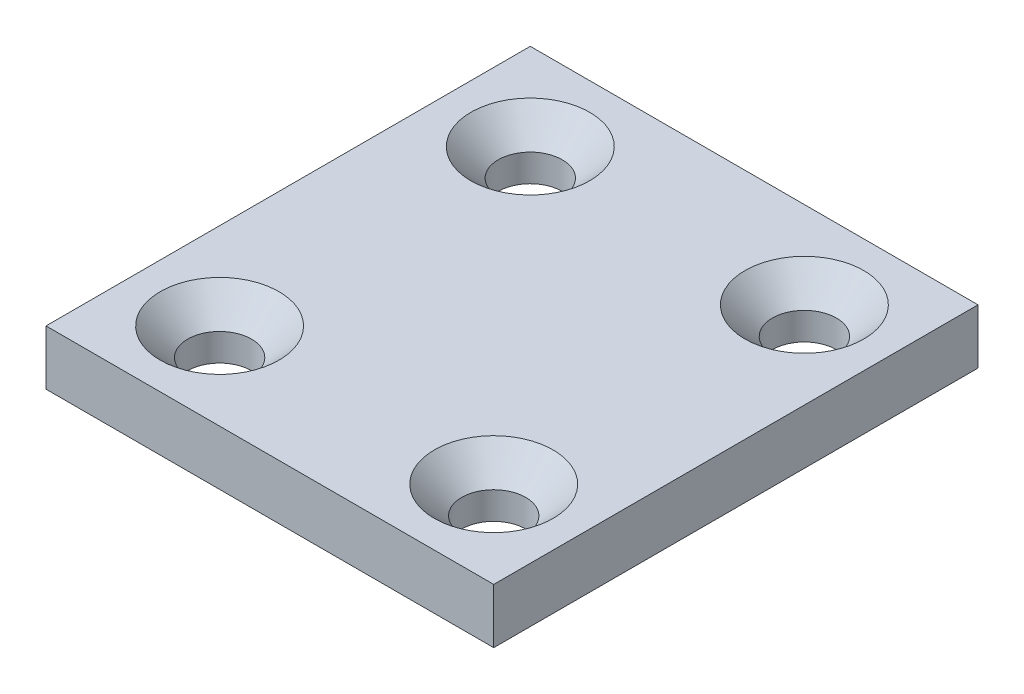
SolidWorks part; units mm, degrees
ref_plane "前视基准面" through (0, 0, 0) normal (0, 0, 1) x (1, 0, 0)
ref_plane "上视基准面" through (0, 0, 0) normal (0, 1, 0) x (1, 0, 0)
ref_plane "右视基准面" through (0, 0, 0) normal (1, 0, 0) x (0, 0, -1)
sketch "草图1" plane through (0, 0, 0) normal (0, 1, 0) x (1, 0, 0)
  line L1 (-4.75, -4.75) -> (19.75, -4.75)
  line L2 (-4.75, -4.75) -> (-4.75, 21.75)
  line L3 (-4.75, 21.75) -> (19.75, 21.75)
  line L4 (19.75, -4.75) -> (19.75, 21.75)
  circle A0 centre (0, 0) radius 1.75
  circle A1 centre (15, 0) radius 1.75
  circle A2 centre (0, 17) radius 1.75
  circle A3 centre (15, 17) radius 1.75
  dimension "D2" = 3.5
  dimension "D3" = 3.5
  dimension "D5" = 3.5
  dimension "D6" = 3.5
  dimension "D10" = 4.75
  dimension "D1" = 15
  dimension "D4" = 15
  dimension "D7" = 17
  dimension "D8" = 24.5
  dimension "D9" = 26.5
  dimension "D11" = 4.75
extrude "凸台-拉伸1" add sketch "草图1" along normal blind 3
hole_wizard "M3 平头机械螺钉的锥形沉头孔1" positions "草图4" profile "草图5" countersink size "M3" standard "ANSI Metric" end condition up to next
sketch "草图4" plane through (0, 3, 0) normal (0, 1, 0) x (1, 0, 0)
  point P0 (0, 0)
  point P3 (15, 0)
  point P6 (15, 17)
  point P9 (0, 17)
sketch "草图5" plane through (0, 3, 0) normal (1, 0, 0) x (0, 0, 1)
  line L0 (0, 0) -> (0, 3)
  line L1 (0, 3) -> (1.6, 3)
  line L2 (1.6, 3) -> (1.6, 1.65)
  line L3 (1.6, 1.65) -> (3.25, 0)
  line L5 (3.25, 0) -> (0, 0)
  line L6 (-1.6, 1.65) -> (-3.25, 0) construction
  line L11 (0, -6.35) -> (0, 107.95) construction
  dimension "通孔孔直径" = 3.2
  dimension "通孔孔深度" = 3
  dimension "近端锥形沉头孔直径" = 6.5
  dimension "近端锥形沉头孔角度" = 90
